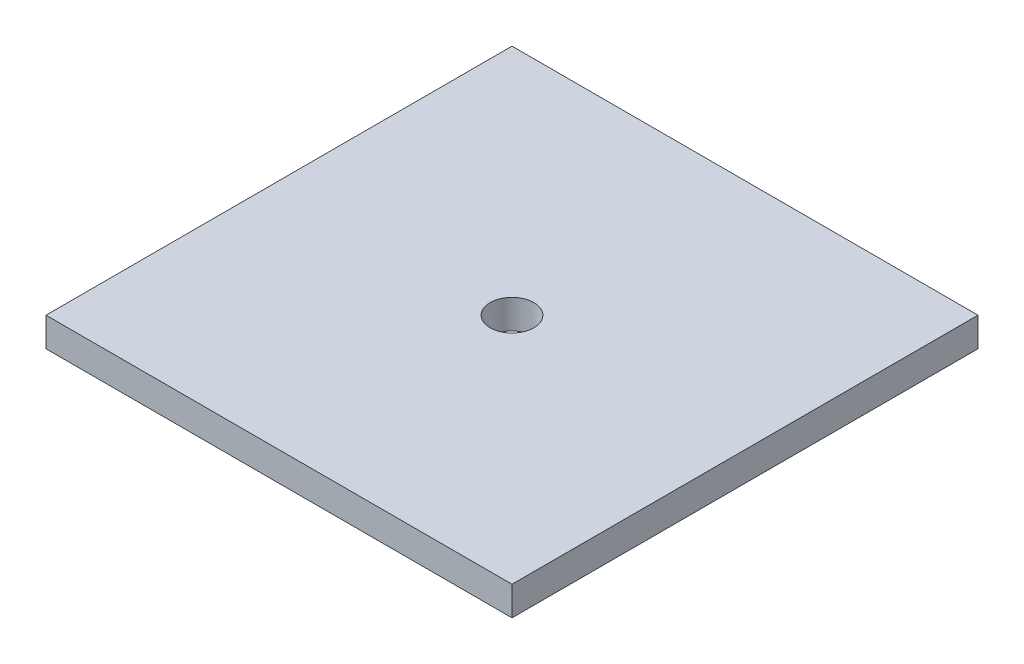
SolidWorks part; units mm, degrees
ref_plane "Front Plane" through (0, 0, 0) normal (0, 0, 1) x (1, 0, 0)
ref_plane "Top Plane" through (0, 0, 0) normal (0, 1, 0) x (1, 0, 0)
ref_plane "Right Plane" through (0, 0, 0) normal (1, 0, 0) x (0, 0, -1)
sketch "Sketch1" plane through (0, 0, 0) normal (0, 1, 0) x (1, 0, 0)
  line L1 (-101.6, -101.6) -> (101.6, -101.6)
  line L2 (-101.6, -101.6) -> (-101.6, 101.6)
  line L3 (-101.6, 101.6) -> (101.6, 101.6)
  line L4 (101.6, -101.6) -> (101.6, 101.6)
  line L5 (-101.6, -101.6) -> (101.6, 101.6) construction
  line L6 (-101.6, 101.6) -> (101.6, -101.6) construction
  circle A0 centre (0, 0) radius 9.525
  point P0 (0, 0)
extrude "Boss-Extrude1" add sketch "Sketch1" along normal blind 12.7
